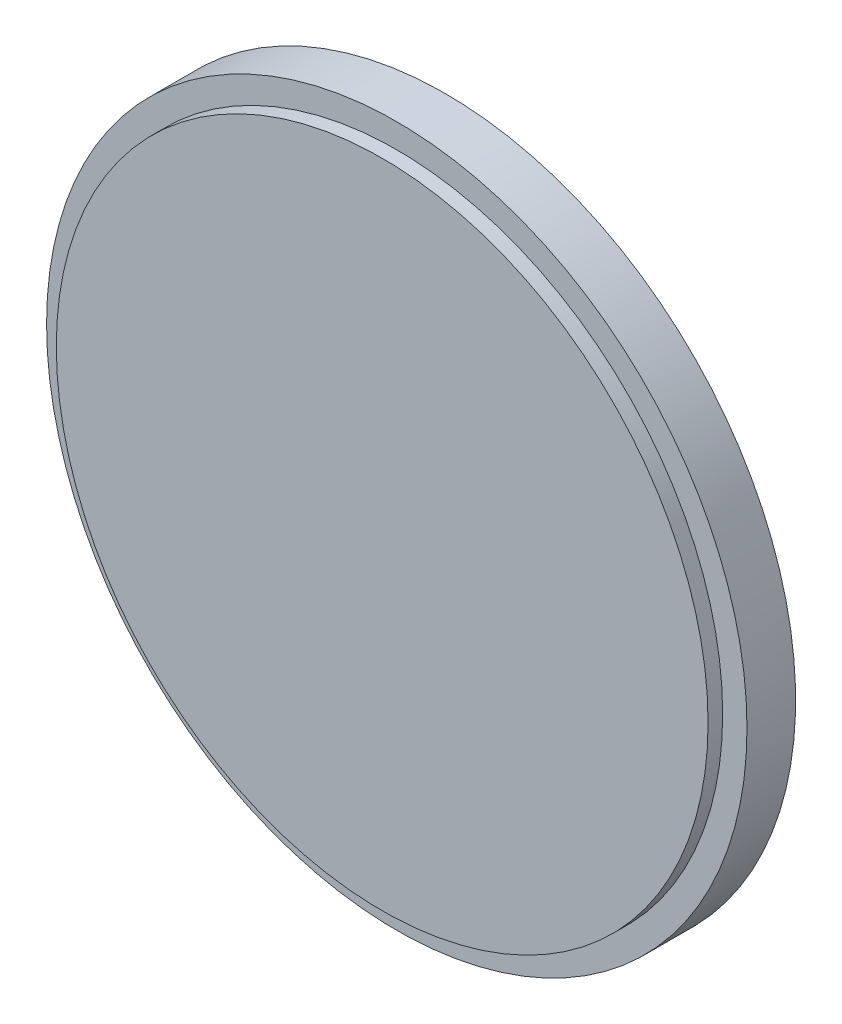
SolidWorks part; units mm, degrees
material "Liga 1060"
ref_plane "Plano frontal" through (0, 0, 0) normal (0, 0, 1) x (1, 0, 0)
ref_plane "Plano superior" through (0, 0, 0) normal (0, 1, 0) x (1, 0, 0)
ref_plane "Plano direito" through (0, 0, 0) normal (1, 0, 0) x (0, 0, -1)
sketch "Esboço1" plane through (0, 0, 0) normal (0, 0, 1) x (1, 0, 0)
  circle A0 centre (0, 0) radius 32.5
  circle A1 centre (0, 0) radius 35
extrude "Ressalto-extrusão1" add sketch "Esboço1" along normal blind 8
sketch "Esboço2" plane through (0, 0, 8) normal (0, 0, 1) x (1, 0, 0)
  circle A0 centre (0, 0) radius 32.5
extrude "Ressalto-extrusão2" add sketch "Esboço2" against normal blind 3
sketch "Esboço3" plane through (0, 0, 8) normal (0, 0, 1) x (1, 0, 0)
  circle A0 centre (0, 0) radius 2.5
extrude "Corte-extrusão1" cut sketch "Esboço3" against normal blind 3
sketch "Esboço4" plane through (0, 0, 5) normal (0, 0, -1) x (-1, 0, 0)
  circle A0 centre (0, 0) radius 37
  circle A1 centre (0, 0) radius 35
extrude "Ressalto-extrusão3" add sketch "Esboço4" against normal through all and the other way through all
sketch "Esboço5" plane through (0, 0, 0) normal (0, 1, 0) x (1, 0, 0)
  line L0 (-37, -1) -> (-37, -7)
  line L1 (-37, -4) -> (-13.2615, -4)
  line L2 (-35.2, -4) -> (-35.2, -1)
  line L3 (-35.2, -1) -> (-37, -1)
  line L4 (-35.2, -4) -> (-35.2, -7)
  line L5 (-35.2, -7) -> (-37, -7)
revolve "Corte-Revolução1" cut sketch "Esboço5" angle 360 about axis through (0, 0, 8) along (0, 0, -1)
sketch "Esboço6" plane through (0, 0, 5) normal (0, 0, -1) x (-1, 0, 0)
  circle A0 centre (0, 0) radius 12.55
  dimension "D1" = 25.1
extrude "Ressalto-extrusão4" add sketch "Esboço6" along normal blind 5
sketch "Esboço7" plane through (0, 0, 0) normal (0, 0, -1) x (-1, 0, 0)
  circle A0 centre (0, 0) radius 7.55
  dimension "D1" = 15.1
extrude "Corte-extrusão2" cut sketch "Esboço7" against normal through all both and the other way through all
sketch "Esboço8" plane through (0, 0, 8) normal (0, 0, 1) x (1, 0, 0)
  circle A0 centre (0, 0) radius 37
  circle A1 centre (0, 0) radius 32.5
  dimension "D1" = 74
extrude "Ressalto-extrusão5" add sketch "Esboço8" against normal up to surface (8 mm away) up to face at (32.5, 0, 0)
sketch "Esboço9" plane through (0, 0, 8) normal (0, 0, 1) x (1, 0, 0)
  circle A0 centre (0, 0) radius 37
  circle A1 centre (0, 0) radius 33.5
extrude "Corte-extrusão8" cut sketch "Esboço9" against normal blind 1.5
sketch "Esboço12" plane through (0, 0, 0) normal (0, 0, -1) x (-1, 0, 0)
  circle A0 centre (0, 0) radius 37
  circle A1 centre (0, 0) radius 33.5
  dimension "D1" = 74
extrude "Corte-extrusão9" cut sketch "Esboço12" against normal blind 1.5
sketch "Esboço13" plane through (0, 0, 1.5) normal (0, 0, -1) x (-1, 0, 0)
  circle A1 centre (0, 0) radius 36
  circle A2 centre (0, 0) radius 37
extrude "Corte-extrusão10" cut sketch "Esboço13" against normal blind 10
sketch "Esboço14" plane through (0, 0, 6.5) normal (0, 0, 1) x (1, 0, 0)
  circle A0 centre (0, 0) radius 37
  circle A1 centre (0, 0) radius 36
  circle A3 centre (0, 0) radius 36
  circle A6 centre (0, 0) radius 36
  circle M3 centre (0, 0) radius 36
  dimension "D1" = 0
extrude "Ressalto-extrusão6" add sketch "Esboço14" against normal up to surface (5 mm away) contours A0 M3 up to face at (-33.5, 0, 1.5)
sketch "Esboço15" plane through (0, 0, 0) normal (0, 0, -1) x (-1, 0, 0)
  circle A0 centre (0, 0) radius 12.55
extrude "Corte-extrusão11" cut sketch "Esboço15" against normal through all
sketch "Esboço16" plane through (0, 0, 5) normal (0, 0, -1) x (-1, 0, 0)
  circle A0 centre (0, 0) radius 12.55 construction
  circle A1 centre (0, 0) radius 12.55
extrude "Ressalto-extrusão7" add sketch "Esboço16" against normal through all
sketch "Esboço17" plane through (0, 0, 5) normal (0, 0, -1) x (-1, 0, 0)
  circle A0 centre (0, 0) radius 10
  dimension "D1" = 20
extrude "Ressalto-extrusão8" add sketch "Esboço17" along normal blind 16
sketch "Esboço18" plane through (0, 0, -11) normal (0, 0, -1) x (-1, 0, 0)
  circle A0 centre (0, 0) radius 3.3
  dimension "D1" = 6.6
extrude "Corte-extrusão12" cut sketch "Esboço18" against normal blind 16
sketch "Esboço19" plane through (0, 0, -11) normal (0, 0, -1) x (-1, 0, 0)
  line L0 (0, -3.3) -> (0, -5.3) construction
  line L1 (-2.975, -5.3) -> (2.975, -5.3)
  line L2 (2.975, -5.3) -> (2.975, -7.95)
  line L3 (2.975, -7.95) -> (-2.975, -7.95)
  line L4 (-2.975, -7.95) -> (-2.975, -5.3)
  line L5 (-3.3, 0) -> (3.3, 0) construction
  line L6 (-2.975, 7.95) -> (-2.975, 5.3)
  line L7 (2.975, 7.95) -> (-2.975, 7.95)
  line L8 (2.975, 5.3) -> (2.975, 7.95)
  line L9 (-2.975, 5.3) -> (2.975, 5.3)
  circle A1 centre (0, 0) radius 3.3 construction
  circle A2 centre (0, 0) radius 3.3 construction
  point P12 (0, -5.3)
  point P19 (0, 5.3)
  dimension "D1" = 2
  dimension "D2" = 5.95
  dimension "D3" = 2.65
extrude "Corte-extrusão13" cut sketch "Esboço19" against normal blind 8
sketch "Esboço23" plane through (0, 0, 1.5) normal (0, 0, -1) x (-1, 0, 0)
  circle A0 centre (0, 0) radius 36
  circle A1 centre (0, 0) radius 37 construction
  circle A2 centre (0, 0) radius 37
  dimension "D1" = 72
extrude "Corte-extrusão15" cut sketch "Esboço23" against normal through all
sketch "Esboço24" plane through (0, 0, -11) normal (0, 0, -1) x (-1, 0, 0)
  line L0 (0, 0) -> (0, 1.1) construction
  line L1 (-1.2298, 1.1) -> (1.2298, 1.1)
  arc A0 (-1.2298, 1.1) -> (1.2298, 1.1) centre (0, 0) ccw
  circle A1 centre (0, 0) radius 3.3 construction
  circle A2 centre (0, 0) radius 3.3
  point P7 (0, 1.1)
  dimension "D1" = 3.3
  dimension "D2" = 1.1
extrude "Ressalto-extrusão9" add sketch "Esboço24" against normal blind 11
sketch "Esboço21" plane through (0, 5.3, 0) normal (0, 1, 0) x (1, 0, 0)
  line L0 (0, 11) -> (0, 8.5) construction
  line L1 (-2.975, 11) -> (2.975, 11) construction
  circle A0 centre (0, 6.85) radius 1.65
  dimension "D2" = 3.3
  dimension "D1" = 2.5
extrude "Corte-extrusão14" cut sketch "Esboço21" against normal through all both and the other way through all
